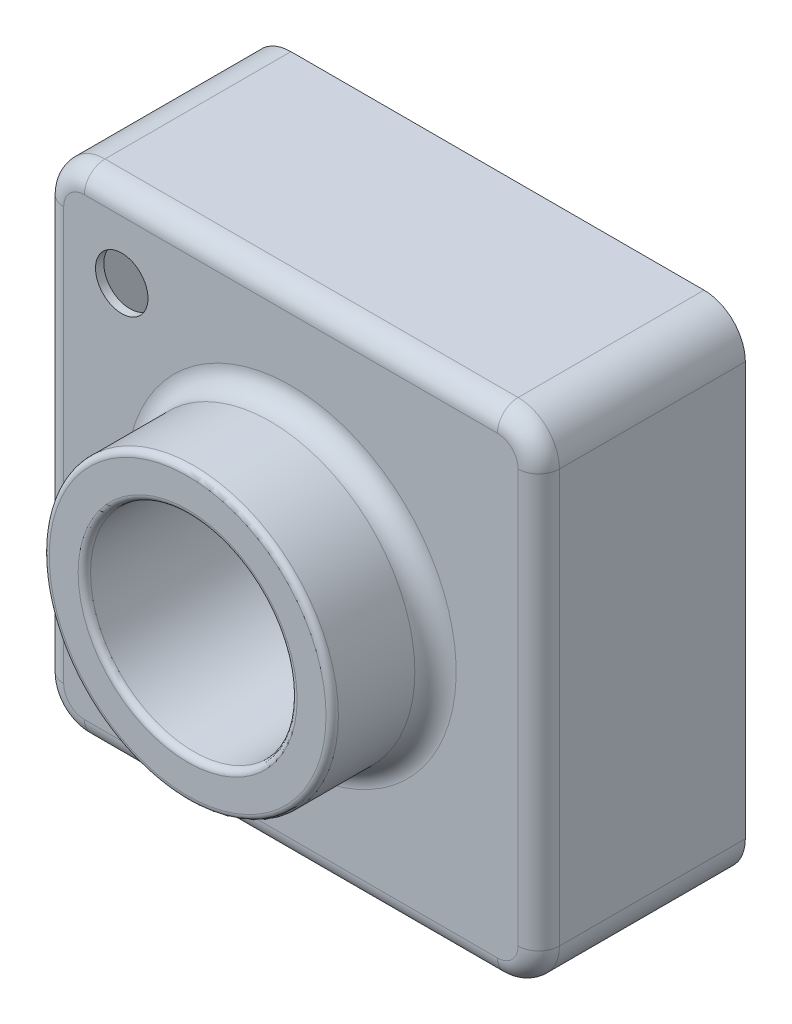
SolidWorks part; units mm, degrees
material "Chrome Stainless Steel"
ref_plane "Front Plane" through (0, 0, 0) normal (0, 0, 1) x (1, 0, 0)
ref_plane "Top Plane" through (0, 0, 0) normal (0, 1, 0) x (1, 0, 0)
ref_plane "Right Plane" through (0, 0, 0) normal (1, 0, 0) x (0, 0, -1)
sketch "Sketch1" plane through (0, 0, 0) normal (0, 0, 1) x (1, 0, 0)
  line L1 (0, 0) -> (120, 0)
  line L2 (0, 0) -> (0, 120)
  line L3 (0, 120) -> (120, 120)
  line L4 (120, 0) -> (120, 120)
  dimension "D1" = 120
  dimension "D2" = 120
extrude "Boss-Extrude1" add sketch "Sketch1" along normal blind 50
sketch "Sketch3" plane through (0, 0, 50) normal (0, 0, 1) x (1, 0, 0)
  line L0 (120, 120) -> (0, 120) construction
  line L1 (120, 0) -> (120, 120) construction
  circle A0 centre (60, 60) radius 35
  dimension "D1" = 70
  dimension "D2" = 60
  dimension "D3" = 60
extrude "Boss-Extrude2" add sketch "Sketch3" along normal blind 25
sketch "Sketch6" plane through (0, 0, 75) normal (0, 0, 1) x (1, 0, 0)
  circle A0 centre (60, 60) radius 25
  dimension "D1" = 50
extrude "Cut-Extrude1" cut sketch "Sketch6" against normal through all
fillet "Fillet1" radius 10 4 edges at (0, 120, 25) (0, 0, 25) (120, 0, 25) (120, 120, 25)
fillet "Fillet2" radius 1.5 2 edges at (95, 60, 75) (85, 60, 75)
fillet "Fillet3" radius 5 9 edges at (117.0711, 117.0711, 50) (120, 60, 50) (117.0711, 2.9289, 50) (60, 0, 50) (2.9289, 2.9289, 50) (0, 60, 50) (2.9289, 117.0711, 50) (60, 120, 50) (95, 60, 50)
shell "Shell1" thickness 2
extrude "Cut-Extrude2" cut sketch "Sketch7" against normal through all
sketch "Sketch7" plane through (92.803, -8.4469, 50) normal (0, 0, 1) x (1, 0, 0)
  circle A0 centre (-73.753, 109.3969) radius 6.35
